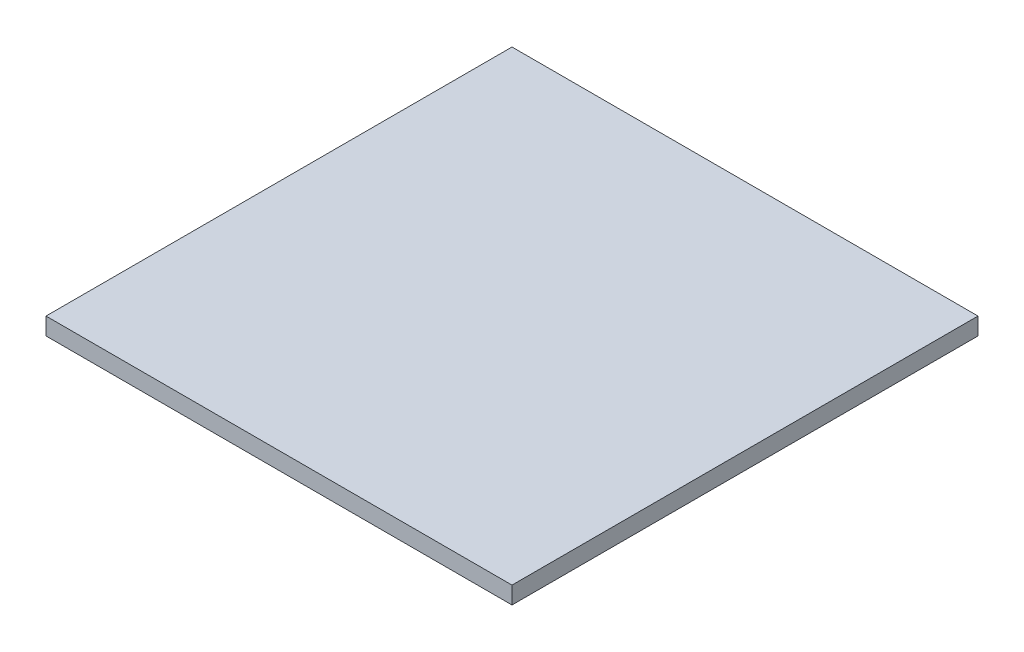
SolidWorks part; units mm, degrees
ref_plane "Front Plane" through (0, 0, 0) normal (0, 0, 1) x (1, 0, 0)
ref_plane "Top Plane" through (0, 0, 0) normal (0, 1, 0) x (1, 0, 0)
ref_plane "Right Plane" through (0, 0, 0) normal (1, 0, 0) x (0, 0, -1)
sketch "Sketch1" plane through (0, 0, 0) normal (0, 1, 0) x (1, 0, 0)
  line L1 (-135, 135) -> (135, 135)
  line L2 (-135, 135) -> (-135, -135)
  line L3 (-135, -135) -> (135, -135)
  line L4 (135, 135) -> (135, -135)
  line L5 (-135, 135) -> (135, -135) construction
  line L6 (-135, -135) -> (135, 135) construction
  point P0 (0, 0)
  dimension "D1" = 270
  dimension "D2" = 270
extrude "Boss-Extrude1" add sketch "Sketch1" along normal blind 10
